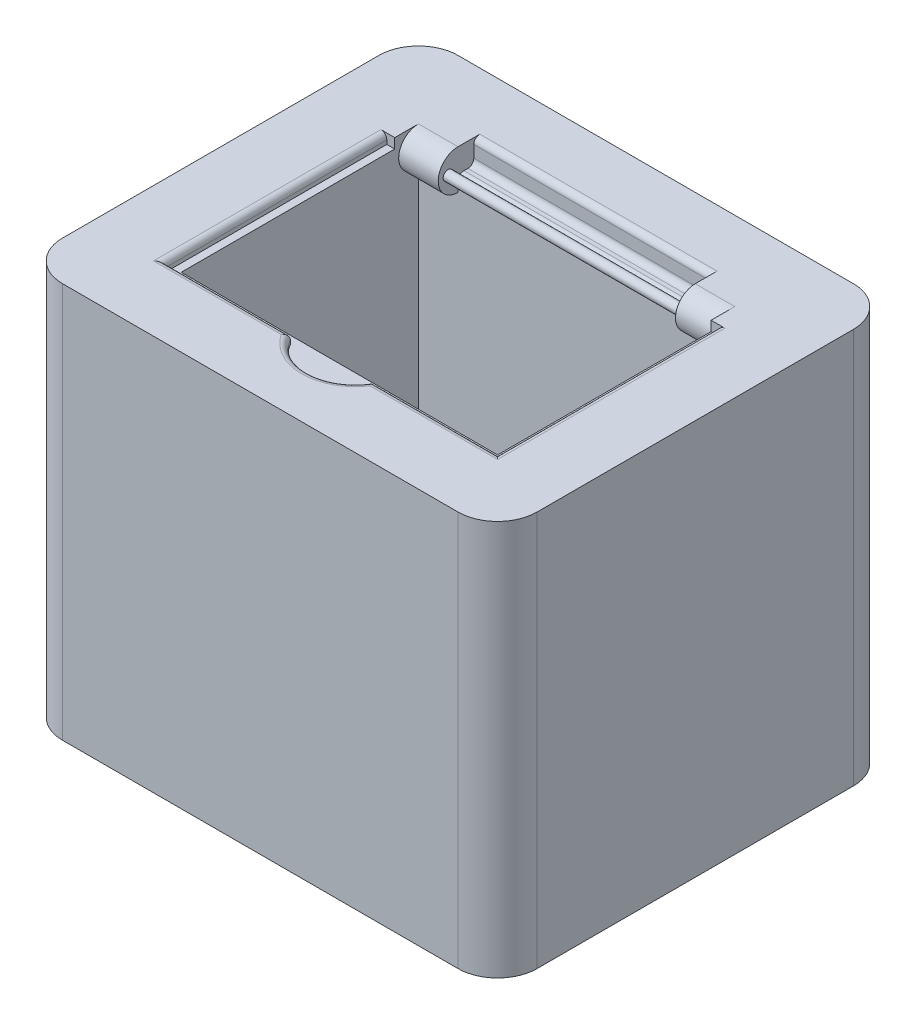
SolidWorks part; units mm, degrees
ref_plane "Front Plane" through (0, 0, 0) normal (0, 0, 1) x (1, 0, 0)
ref_plane "Top Plane" through (0, 0, 0) normal (0, 1, 0) x (1, 0, 0)
ref_plane "Right Plane" through (0, 0, 0) normal (1, 0, 0) x (0, 0, -1)
sketch "Sketch1" plane through (0, 0, 0) normal (0, 1, 0) x (1, 0, 0)
  line L1 (-60, 50) -> (60, 50)
  line L2 (-60, 50) -> (-60, -50)
  line L3 (-60, -50) -> (60, -50)
  line L4 (60, 50) -> (60, -50)
  point P4 (0, 0)
  dimension "D1" = 60
  dimension "D2" = 50
  dimension "D3" = 120
  dimension "D4" = 100
extrude "Boss-Extrude1" add sketch "Sketch1" along normal blind 90 and the other way blind 10
fillet "Fillet1" radius 10 4 edges at (60, 40, -50) (-60, 40, -50) (-60, 40, 50) (60, 40, 50)
sketch "Sketch2" plane through (0, 90, 0) normal (0, 1, 0) x (1, 0, 0)
  line L8 (40, -30) -> (40, 30)
  line L9 (40, 30) -> (-40, 30)
  line L10 (-40, 30) -> (-40, -30)
  line L11 (-40, -30) -> (40, -30)
  line L12 (40, -30) -> (40, 30)
  line L13 (40, 30) -> (-40, 30)
  line L14 (-40, 30) -> (-40, -30)
  line L15 (-40, -30) -> (40, -30)
  dimension "D1" = 20
extrude "Cut-Extrude1" cut sketch "Sketch2" against normal through all
sketch "Sketch3" plane through (0, -10, 0) normal (0, -1, 0) x (1, 0, 0)
  line L4 (53.1, 43.1) -> (-53.1, 43.1)
  line L5 (-53.1, 43.1) -> (-53.1, -43.1)
  line L6 (-53.1, -43.1) -> (53.1, -43.1)
  line L7 (53.1, -43.1) -> (53.1, 43.1)
  line L8 (-50, -40) -> (50, -40)
  line L9 (50, -40) -> (50, 40)
  line L10 (50, 40) -> (-50, 40)
  line L11 (-50, 40) -> (-50, -40)
  line L12 (-50, -40) -> (50, -40) construction
  line L13 (50, -40) -> (50, 40) construction
  line L14 (50, 40) -> (-50, 40) construction
  line L15 (-50, 40) -> (-50, -40) construction
  line L16 (46.9, 36.9) -> (-46.9, 36.9)
  line L17 (-46.9, 36.9) -> (-46.9, -36.9)
  line L18 (-46.9, -36.9) -> (46.9, -36.9)
  line L19 (46.9, -36.9) -> (46.9, 36.9)
  dimension "D1" = 10
  dimension "D2" = 3.1
  dimension "D3" = 3.1
extrude "Cut-Extrude2" cut sketch "Sketch3" against normal blind 10
sketch "Sketch4" plane through (60, 0, 0) normal (1, 0, 0) x (0, 0, -1)
  line L0 (30, 80) -> (30, 90)
  line L1 (-40, 90) -> (40, 90) construction
  arc A0 (30, 90) -> (30, 80) centre (30, 85) ccw
  point P0 (30, 90)
  dimension "D1" = 5
  dimension "D2" = 10
extrude "Boss-Extrude3" add sketch "Sketch4" against normal up to surface (80 mm away) from offset 20 up to face at (-40, 40, 0) offset against normal yes
sketch "Sketch5" plane through (60, 0, 0) normal (1, 0, 0) x (0, 0, -1)
  line L0 (30, 80) -> (30, 90) construction
  line L1 (30, 80) -> (30, 90)
  line L2 (-40, 90) -> (40, 90) construction
  arc A0 (30, 90) -> (30, 80) centre (30, 85) ccw
  circle A1 centre (27.5, 85) radius 1.25
  dimension "D2" = 2.5
  dimension "D1" = 2.5
  dimension "D3" = 5
extrude "Cut-Extrude3" cut sketch "Sketch5" against normal blind 60 from offset 30 offset against normal yes
sketch "Sketch6" plane through (0, 90, 0) normal (0, 1, 0) x (1, 0, 0)
  line L0 (-40, -30) -> (-40, 24)
  line L1 (-40, 30) -> (-40, -30) construction
  line L3 (40, -30) -> (40, 30) construction
  line L4 (40, 24) -> (40, -30)
  line L5 (40, -30) -> (-40, -30)
  line L6 (42, 24) -> (42, -32)
  line L7 (42, -32) -> (10.3923, -32)
  line L8 (-42, -32) -> (-42, 24)
  line L9 (40, 24) -> (42, 24)
  line L10 (-40, 24) -> (-42, 24)
  line L11 (0, -26) -> (0, -30) construction
  line L12 (-10.3923, -32) -> (-42, -32)
  line L14 (42, -32) -> (-42, -32) construction
  arc A0 (-10.3923, -32) -> (10.3923, -32) centre (0, -26) ccw
  point P14 (0, -30)
  point P15 (0, -26)
  dimension "D5" = 12
  dimension "D1" = 2
  dimension "D2" = 56
  dimension "D3" = 56
  dimension "D4" = 4
extrude "Cut-Extrude4" cut sketch "Sketch6" against normal blind 2.5
sketch "Sketch7" plane through (0, 90, 0) normal (0, 1, 0) x (1, 0, 0)
  line L0 (-30, 30) -> (30, 30)
  line L1 (30, 30) -> (30, 34)
  line L2 (30, 34) -> (-30, 34)
  line L3 (-30, 34) -> (-30, 30)
  dimension "D1" = 4
extrude "Cut-Extrude5" cut sketch "Sketch7" against normal blind 6
fillet "Fillet2" radius 1.5 8 edges at (0, 90, -34) (42, 90, 4) (-42, 90, 4) (26.1962, 90, 32) (-26.1962, 90, 32) (0, 90, 38) (0, 84, -30) (0, 84, -34)
equation "\"X\"=120"
equation "\"D3@Sketch1\"=\"X\""
equation "\"Y\"=100"
equation "\"D4@Sketch1\"=\"Y\""
equation "\"Z\"=100"
equation "\"D1@Boss-Extrude1\"=\"Z\"-10"
